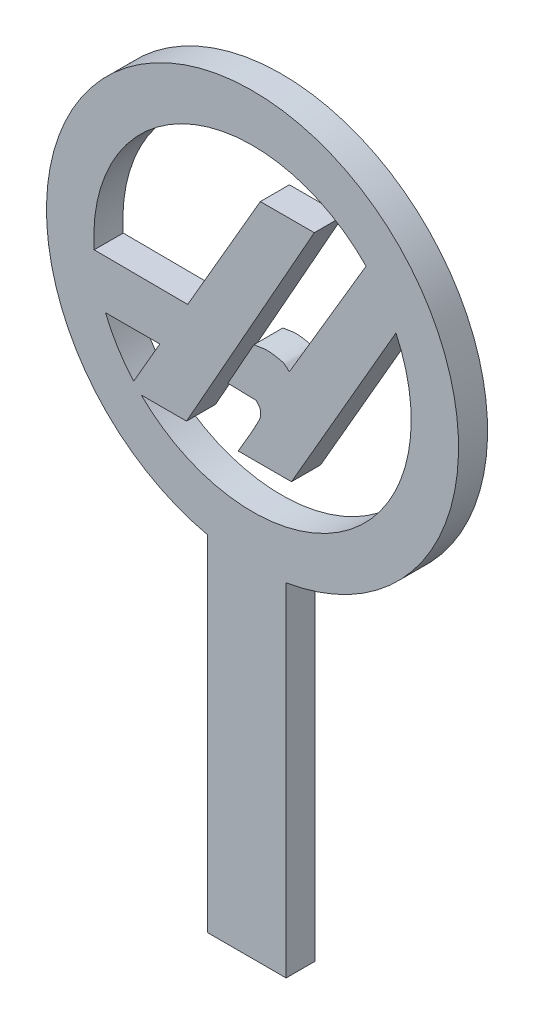
SolidWorks part; units mm, degrees
ref_plane "Front Plane" through (0, 0, 0) normal (0, 0, 1) x (1, 0, 0)
ref_plane "Top Plane" through (0, 0, 0) normal (0, 1, 0) x (1, 0, 0)
ref_plane "Right Plane" through (0, 0, 0) normal (1, 0, 0) x (0, 0, -1)
sketch "Sketch1" plane through (0, 0, 0) normal (0, 0, 1) x (1, 0, 0)
  line L0 (153.6667, 407) -> (768.3333, 407) construction
  line L1 (136.6667, 381.5) -> (683.3333, 381.5) construction
  line L5 (652.1845, 561.6969) -> (520, 338)
  line L6 (459, 348) -> (414.1531, 268)
  line L7 (414.1531, 268) -> (463, 267)
  line L8 (432, 176) -> (523.7837, 176)
  line L9 (523.7837, 176) -> (703.6075, 487.7876)
  line L10 (264.9969, 175.9694) -> (342.9994, 176)
  line L11 (342.9994, 176) -> (563, 567)
  line L12 (563, 567) -> (470.0808, 567)
  line L13 (470.0808, 567) -> (345, 351)
  line L14 (345, 351) -> (184, 352)
  line L15 (203.4239, 268) -> (297, 268)
  line L16 (297, 268) -> (251.8843, 189.7995)
  line L17 (514.5212, -568.699) -> (379.3828, -568.699)
  line L19 (514.5212, -568.699) -> (514.5212, 20.7591)
  line L21 (379.3828, -568.699) -> (379.3828, 24.5172)
  arc A0 (514.5212, 20.7591) -> (379.3828, 24.5172) centre (456.634, 370.7972) ccw
  arc A1 (203.4239, 268) -> (251.8843, 189.7995) centre (456.634, 370.7972) ccw
  arc A2 (264.9969, 175.9694) -> (703.6075, 487.7876) centre (456.634, 370.7972) ccw
  arc A3 (652.1845, 561.6969) -> (184, 352) centre (456.634, 370.7972) ccw
  spline S2 degree 3 poles (520, 338) (516, 341) (512.8565, 345.8107) (508, 347) (483.2942, 353.0504) (477.8517, 351.142) (459, 348) knots 0 0 0 0 1 1 1 2 2 2 2
  spline S3 degree 3 poles (463, 267) (465.3333, 263.6667) (469.0504, 260.9565) (470, 257) (471.1695, 252.1273) (471.1283, 246.5367) (469, 242) (458.288, 219.1666) (444.3333, 198) (432, 176) knots 0 0 0 0 1 1 1 2 2 2 3 3 3 3
extrude "Boss-Extrude1" add sketch "Sketch1" along normal blind 50
